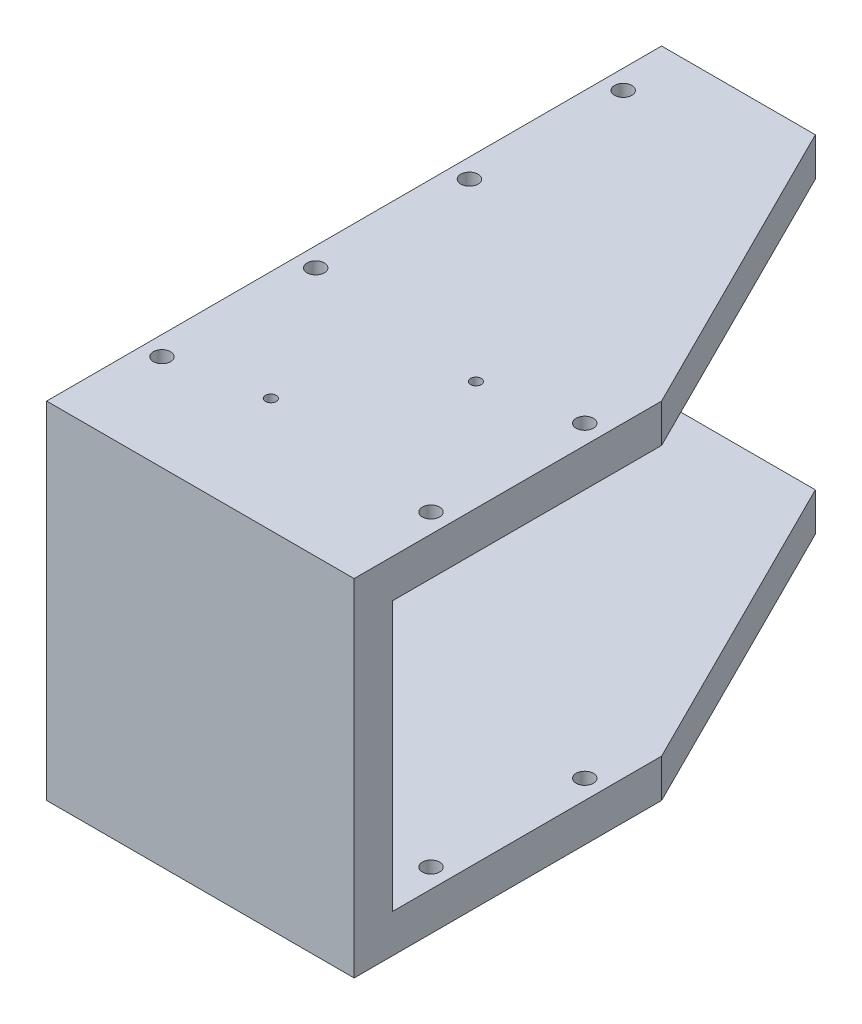
SolidWorks part; units mm, degrees
material "ABS"
ref_plane "Alzado" through (0, 0, 0) normal (0, 0, 1) x (1, 0, 0)
ref_plane "Planta" through (0, 0, 0) normal (0, 1, 0) x (1, 0, 0)
ref_plane "Vista lateral" through (0, 0, 0) normal (1, 0, 0) x (0, 0, -1)
sketch "Croquis1" plane through (0, 0, 0) normal (0, 1, 0) x (1, 0, 0)
  line L0 (0, 0) -> (0, 80)
  line L1 (0, 80) -> (-40, 160)
  line L2 (-40, 160) -> (-80, 160)
  line L3 (-80, 160) -> (-80, 0)
  line L4 (-80, 0) -> (0, 0)
  dimension "D1" = 80
  dimension "D2" = 80
  dimension "D3" = 160
  dimension "D4" = 40
extrude "Saliente-Extruir1" add sketch "Croquis1" along normal blind 10
sketch "Croquis2" plane through (0, 10, 0) normal (0, 1, 0) x (1, 0, 0)
  line L0 (-80, 0) -> (-80, 10)
  line L1 (-80, 160) -> (-80, 0) construction
  line L2 (-80, 10) -> (0, 10)
  line L3 (0, 0) -> (0, 80) construction
  line L4 (0, 10) -> (0, 0)
  line L5 (0, 0) -> (-80, 0)
  dimension "D1" = 10
extrude "Saliente-Extruir2" add sketch "Croquis2" along normal blind 70
sketch "Croquis3" plane through (0, 80, 0) normal (0, 1, 0) x (1, 0, 0)
  line L5 (-80, 0) -> (0, 0)
  line L6 (-80, 160) -> (-80, 0)
  line L7 (-40, 160) -> (-80, 160)
  line L8 (0, 80) -> (-40, 160)
  line L9 (0, 0) -> (0, 80)
  line L10 (-80, 0) -> (0, 0)
  line L11 (-80, 160) -> (-80, 0)
  line L12 (-40, 160) -> (-80, 160)
  line L13 (0, 80) -> (-40, 160)
  line L14 (0, 0) -> (0, 80)
  dimension "D1" = 0
extrude "Saliente-Extruir3" add sketch "Croquis3" along normal blind 10
sketch "Croquis4" plane through (0, 90, 0) normal (0, 1, 0) x (1, 0, 0)
  line L0 (-80, 25) -> (-75, 25) construction
  line L1 (-80, 160) -> (-80, 0) construction
  line L2 (-75, 25) -> (-5, 25) construction
  line L3 (-5, 25) -> (0, 25) construction
  line L4 (0, 0) -> (0, 80) construction
  line L5 (-80, 0) -> (0, 0) construction
  line L6 (-75, 25) -> (-75, 65) construction
  line L7 (-75, 65) -> (-5, 65) construction
  line L8 (-5, 65) -> (-5, 25) construction
  line L9 (-75, 65) -> (-75, 105) construction
  line L10 (-75, 105) -> (-75, 145) construction
  line L11 (-75, 145) -> (-75, 160) construction
  line L12 (-40, 160) -> (-80, 160) construction
  circle A0 centre (-75, 25) radius 2.25
  circle A1 centre (-5, 25) radius 2.25
  circle A2 centre (-5, 65) radius 2.25
  circle A3 centre (-75, 65) radius 2.25
  circle A4 centre (-75, 145) radius 2.25
  circle A5 centre (-75, 105) radius 2.25
  dimension "D3" = 4.5
  dimension "D1" = 25
  dimension "D2" = 5
  dimension "D4" = 40
  dimension "D5" = 15
  dimension "D6" = 40
extrude "Cortar-Extruir1" cut sketch "Croquis4" against normal through all
sketch "Croquis5" plane through (0, 90, 0) normal (0, 1, 0) x (1, 0, 0)
  line L0 (-80, 160) -> (-80, 0) construction
  line L1 (-80, 0) -> (0, 0) construction
  line L2 (-51.43, 29.76) -> (-28.57, 29.76) construction
  line L3 (-28.57, 29.76) -> (-28.57, 60.24) construction
  circle A0 centre (-51.43, 29.76) radius 1.4
  circle A1 centre (-28.57, 60.24) radius 1.4
  dimension "D1" = 28.57
  dimension "D2" = 29.76
  dimension "D3" = 2.8
  dimension "D4" = 22.86
  dimension "D5" = 30.48
extrude "Cortar-Extruir2" cut sketch "Croquis5" against normal up to next
